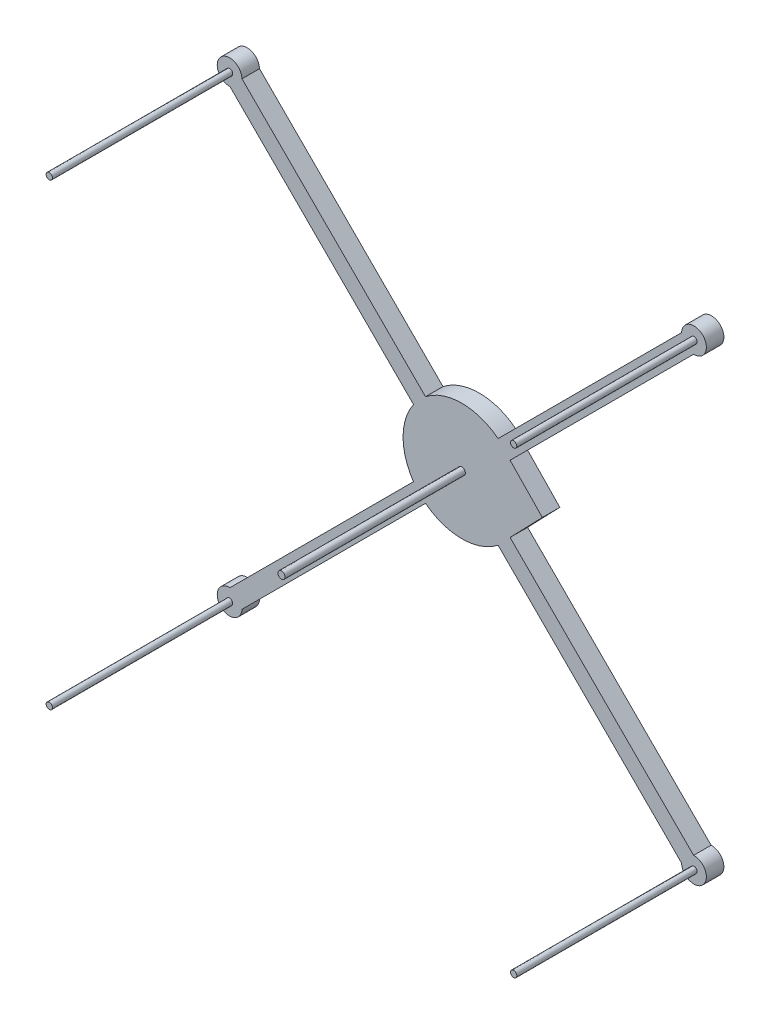
SolidWorks part; units mm, degrees
ref_plane "Front" through (0, 0, 0) normal (0, 0, 1) x (1, 0, 0)
ref_plane "Top" through (0, 0, 0) normal (0, 1, 0) x (1, 0, 0)
ref_plane "Right" through (0, 0, 0) normal (1, 0, 0) x (0, 0, -1)
sketch "Sketch2" plane through (0, 0, 0) normal (0, 0, 1) x (1, 0, 0)
  line L0 (0, 0) -> (0, 50000) construction
  line L1 (0, 0) -> (50000, 0) construction
  line L2 (-20.7223, 26.3812) -> (-125.5536, 131.2125)
  line L3 (27.5804, 19.0972) -> (132.4117, 123.9285)
  line L4 (20.7223, 26.3812) -> (125.5536, 131.2125)
  line L5 (-27.5804, 19.0972) -> (-132.4117, 123.9285)
  line L6 (-27.5804, -19.0972) -> (-132.4117, -123.9285)
  line L7 (20.7223, -26.3812) -> (125.5536, -131.2125)
  line L8 (27.5804, -19.0972) -> (132.4117, -123.9285)
  line L9 (-20.7223, -26.3812) -> (-125.5536, -131.2125)
  line L10 (27.5804, 19.0972) -> (46.005, 0)
  line L11 (46.005, 0) -> (27.5804, -19.0972)
  arc A0 (-20.7223, 26.3812) -> (20.7223, 26.3812) centre (0, 0) cw
  arc A2 (132.4117, 123.9285) -> (125.5536, 131.2125) centre (132.6213, 130.9965) ccw
  arc A3 (-132.4117, 123.9285) -> (-125.5536, 131.2125) centre (-132.6213, 130.9965) cw
  arc A4 (-27.5804, 19.0972) -> (-27.5804, -19.0972) centre (0, 0) ccw
  arc A5 (-132.4117, -123.9285) -> (-125.5536, -131.2125) centre (-132.6213, -130.9965) ccw
  arc A6 (132.4117, -123.9285) -> (125.5536, -131.2125) centre (132.6213, -130.9965) cw
  arc A7 (-20.7223, -26.3812) -> (20.7223, -26.3812) centre (0, 0) ccw
  point P10 (46.005, 0)
extrude "Boss-Extrude1" add sketch "Sketch2" along normal blind 10
sketch "Sketch3" plane through (0, 0, 0) normal (0, 0, 1) x (1, 0, 0)
  line L0 (0, 136.9984) -> (0, -120.6055) construction
  line L1 (-95.5142, 0) -> (151.7187, 0) construction
  circle A0 centre (-132.6213, 130.9965) radius 1.7969
  circle A1 centre (132.6213, 130.9965) radius 1.7969
  circle A2 centre (132.6213, -130.9965) radius 1.7969
  circle A3 centre (-132.6213, -130.9965) radius 1.7969
  circle A4 centre (0, 0) radius 2.0387
extrude "Boss-Extrude2" add sketch "Sketch3" along normal blind 113
